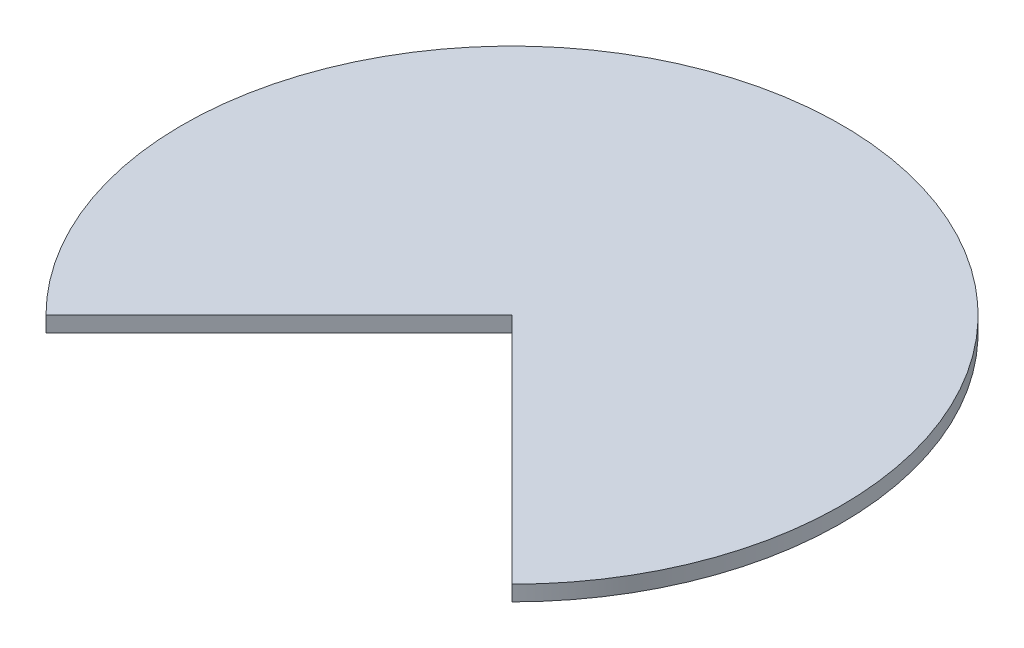
SolidWorks part; units mm, degrees
ref_plane "Front Plane" through (0, 0, 0) normal (0, 0, 1) x (1, 0, 0)
ref_plane "Top Plane" through (0, 0, 0) normal (0, 1, 0) x (1, 0, 0)
ref_plane "Right Plane" through (0, 0, 0) normal (1, 0, 0) x (0, 0, -1)
sketch "Sketch1" plane through (0, 0, 0) normal (0, 1, 0) x (1, 0, 0)
  line L0 (0, 0) -> (-96.5168, -96.5168)
  line L1 (0, 0) -> (96.5168, -96.5168)
  line L2 (0, 0) -> (0, -50000) construction
  arc A0 (96.5168, -96.5168) -> (-96.5168, -96.5168) centre (0, 0) ccw
extrude "Boss-Extrude1" add sketch "Sketch1" along normal blind 6.35
